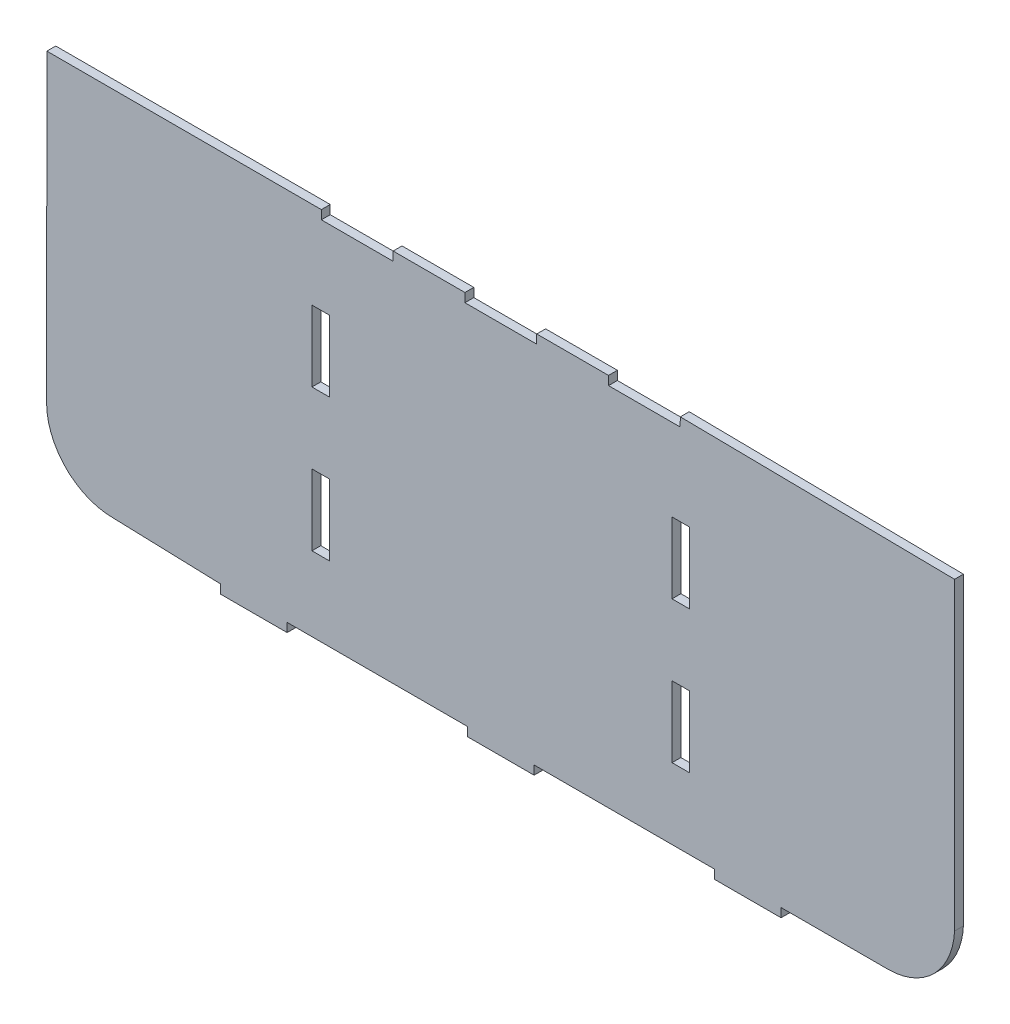
SolidWorks part; units mm, degrees
ref_plane "Front Plane" through (0, 0, 0) normal (0, 0, 1) x (1, 0, 0)
ref_plane "Top Plane" through (0, 0, 0) normal (0, 1, 0) x (1, 0, 0)
ref_plane "Right Plane" through (0, 0, 0) normal (1, 0, 0) x (0, 0, -1)
sketch "Sketch1" plane through (0, 0, 0) normal (0, 0, 1) x (1, 0, 0)
  line L12 (-444.5, 10.16) -> (-321.2, 6.2241)
  line L16 (-245, 6.2241) -> (-38.1, 6.2241)
  line L20 (38.1, 6.2241) -> (245, 6.2241)
  line L27 (205.7064, 435.61) -> (205.558, 425.45)
  line L28 (205.558, 425.45) -> (123.444, 425.45)
  line L29 (123.444, 425.45) -> (123.444, 435.61)
  line L30 (123.444, 435.61) -> (41.148, 435.61)
  line L31 (41.148, 435.61) -> (41.148, 425.45)
  line L32 (41.148, 425.45) -> (-41.148, 425.45)
  line L33 (-41.148, 425.45) -> (-41.148, 435.61)
  line L34 (-41.148, 435.61) -> (-123.444, 435.61)
  line L35 (-123.444, 435.61) -> (-123.444, 425.45)
  line L36 (-123.444, 425.45) -> (-205.74, 425.45)
  line L37 (-205.74, 425.45) -> (-205.74, 388.35)
  line L38 (-205.74, 388.35) -> (-230.3597, 388.35)
  line L39 (-520.3601, 435.61) -> (-520.7, 86.36)
  line L43 (-38.1, 6.2241) -> (-38.1, -3.9359) construction
  line L45 (38.1, 6.2241) -> (38.1, -3.9359) construction
  line L46 (38.1, 6.2241) -> (38.1, -3.9359)
  line L47 (-38.1, 6.2241) -> (-38.1, -3.9359)
  line L48 (245, 6.2241) -> (245, -3.9359) construction
  line L49 (321.2, 6.2241) -> (321.2, -3.9359) construction
  line L50 (245, 6.2241) -> (245, -3.9359)
  line L51 (321.2, 6.2241) -> (321.2, -3.9359)
  line L52 (-245, 6.2241) -> (-245, -3.9359) construction
  line L53 (-321.2, 6.2241) -> (-321.2, -3.9359) construction
  line L54 (-321.2, 6.2241) -> (-321.2, -3.9359)
  line L55 (-245, 6.2241) -> (-245, -3.9359)
  line L56 (216.5353, 168.858) -> (216.5353, 87.541) construction
  line L57 (216.5353, 331.4919) -> (216.5353, 250.1749) construction
  line L58 (216.5353, 168.858) -> (216.5353, 87.541)
  line L59 (216.5353, 331.4919) -> (216.5353, 250.1749)
  line L60 (-205.74, 425.45) -> (-205.74, 435.61)
  line L61 (-205.74, 435.61) -> (-520.3601, 435.61)
  line L62 (-216.5353, 172.7939) -> (-216.5353, 91.4769)
  line L63 (-216.5353, 335.4278) -> (-216.5353, 254.1108)
  line L64 (196.2153, 331.4919) -> (196.2153, 250.1749)
  line L65 (-196.2153, 335.4278) -> (-196.2153, 254.1108)
  line L66 (-196.2153, 172.7939) -> (-196.2153, 91.4769)
  line L67 (196.2153, 168.858) -> (196.2153, 87.541)
  line L68 (196.2153, 331.4919) -> (216.5353, 331.4919)
  line L69 (-196.2153, 335.4278) -> (-216.5353, 335.4278)
  line L70 (-216.5353, 254.1108) -> (-196.2153, 254.1108)
  line L71 (-196.2153, 172.7939) -> (-216.5353, 172.7939)
  line L72 (-196.2153, 91.4769) -> (-216.5353, 91.4769)
  line L73 (196.2153, 87.541) -> (216.5353, 87.541)
  line L74 (216.5353, 168.858) -> (196.2153, 168.858)
  line L75 (216.5353, 250.1749) -> (196.2153, 250.1749)
  line L76 (-520.3601, 435.61) -> (-520.3601, 465.8105)
  line L77 (-520.3601, 465.8105) -> (-530.3597, 465.719)
  line L78 (-530.3597, 465.719) -> (-530.3597, 494.219)
  line L79 (-530.3597, 494.219) -> (-230.3597, 494.219)
  line L81 (321.2, -3.9359) -> (245, -3.9359)
  line L82 (38.1, -3.9359) -> (-38.1, -3.9359)
  line L83 (-245, -3.9359) -> (-321.2, -3.9359)
  line L84 (-230.3597, 494.219) -> (-230.3597, 388.35)
  line L85 (520.0465, 82.2641) -> (520.0703, 431.5141) construction
  line L86 (520.0465, 82.2641) -> (520.0703, 431.5141)
  line L87 (444.5, 6.2241) -> (321.2, 6.2241)
  line L88 (-520.3601, 435.61) -> (580.4446, 435.61) construction
  line L89 (-123.444, 425.45) -> (629.1878, 425.45) construction
  line L90 (205.7064, 435.61) -> (520.0703, 431.5141)
  line L91 (-205.74, 435.61) -> (-230.3597, 435.61)
  line L92 (-230.3597, 435.61) -> (-230.3597, 388.35)
  line L94 (-230.3597, 388.35) -> (-205.74, 388.35)
  line L95 (-230.3597, 388.35) -> (-230.3597, 435.61)
  line L96 (-230.3597, 435.61) -> (-205.74, 435.61)
  line L97 (-205.74, 388.35) -> (-205.74, 435.61)
  arc A0 (-520.7, 86.36) -> (-444.5, 10.16) centre (-444.5, 86.36) ccw
  ellipse E3 centre (443.8465, 86.3572) end of major axis (443.8465, 166.4932) minor radius 76.2996 (444.5, 6.2241) -> (520.0465, 82.2641) ccw
  dimension "D2" = 20.32
  dimension "D1" = 28.5
  dimension "D4" = 20.32
  dimension "D5" = 20.32
  dimension "D6" = 20.32
  dimension "D7" = 300
other "AlignGroup1"
extrude "Boss-Extrude1" add sketch "Sketch1" along normal blind 10.16 contours L87 E3 L86 L90 L27 L28 L29 L30 L31 L32 L33 L34 L35 L36 L37 L38 L84 L61 L39 A0 L12 L54 L83 L55 L16 L47 L82 L46 L20 L50 L81 L51 L59 L75 L64 L68 L66 L72 L62 L71 L70 L63 L69 L65 L74 L58 L73 | L61 L84 L38 L37 L60
